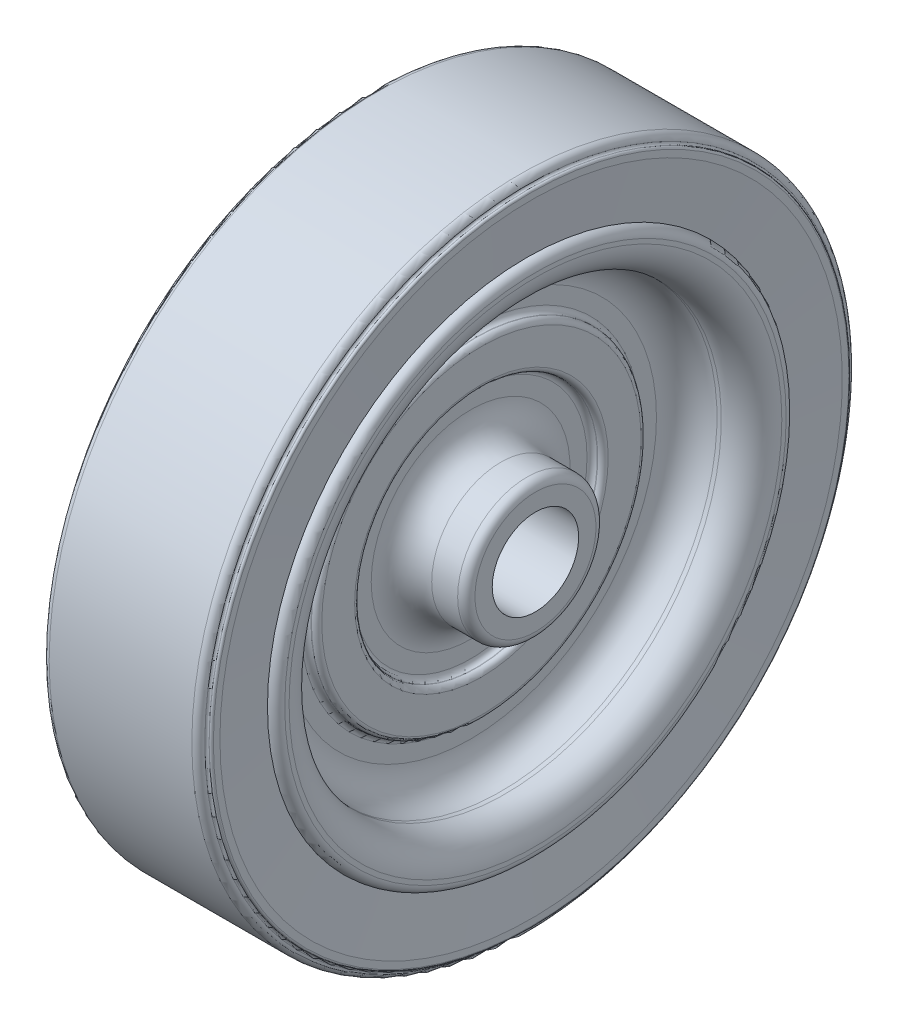
SolidWorks part; units mm, degrees
ref_plane "Front Plane" through (0, 0, 0) normal (0, 0, 1) x (1, 0, 0)
ref_plane "Top Plane" through (0, 0, 0) normal (0, 1, 0) x (1, 0, 0)
ref_plane "Right Plane" through (0, 0, 0) normal (1, 0, 0) x (0, 0, -1)
sketch "Sketch1" plane through (0, 0, 0) normal (0, 0, 1) x (1, 0, 0)
  line L0 (-29.5073, 0) -> (47.8198, 0) construction
  line L1 (4.9928, 38.1359) -> (5.0928, 38.1359)
  line L2 (-19.2072, 16) -> (-13.2072, 16)
  line L3 (-21.2072, 14) -> (-21.2072, 10)
  line L4 (-21.2072, 10) -> (18.7928, 10)
  line L5 (18.7928, 14) -> (18.7928, 10)
  line L9 (-6.2072, 23) -> (-6.2072, 26.9359)
  line L10 (10.7928, 16) -> (16.7928, 16)
  line L11 (3.7928, 23) -> (3.7928, 26.9359)
  line L12 (-14.2072, 50) -> (-13.2072, 50)
  line L13 (-21.2072, 57) -> (-21.2072, 58)
  line L14 (-19.2072, 60) -> (16.7928, 60)
  line L15 (18.7928, 57) -> (18.7928, 58)
  line L16 (-7.5072, 38.1359) -> (-7.4072, 38.1359)
  line L17 (-8.7072, 36.9359) -> (-8.7072, 29.3359)
  line L18 (-7.5072, 28.1359) -> (-7.4072, 28.1359)
  line L19 (6.2928, 36.9359) -> (6.2928, 29.3359)
  line L20 (10.7928, 50) -> (11.7928, 50)
  line L22 (-6.2072, 39.3359) -> (-6.2072, 43)
  line L24 (4.9928, 28.1359) -> (5.0928, 28.1359)
  line L25 (3.7928, 39.3359) -> (3.7928, 43)
  arc A0 (16.7928, 16) -> (18.7928, 14) centre (16.7928, 14) cw
  arc A1 (-19.2072, 16) -> (-21.2072, 14) centre (-19.2072, 14) ccw
  arc A2 (16.7928, 60) -> (18.7928, 58) centre (16.7928, 58) cw
  arc A3 (-21.2072, 58) -> (-19.2072, 60) centre (-19.2072, 58) cw
  arc A4 (10.7928, 16) -> (3.7928, 23) centre (10.7928, 23) cw
  arc A5 (-13.2072, 16) -> (-6.2072, 23) centre (-13.2072, 23) ccw
  arc A6 (11.7928, 50) -> (18.7928, 57) centre (11.7928, 57) ccw
  arc A7 (3.7928, 43) -> (10.7928, 50) centre (10.7928, 43) cw
  arc A8 (-13.2072, 50) -> (-6.2072, 43) centre (-13.2072, 43) cw
  arc A9 (-14.2072, 50) -> (-21.2072, 57) centre (-14.2072, 57) cw
  arc A10 (4.9928, 38.1359) -> (3.7928, 39.3359) centre (4.9928, 39.3359) cw
  arc A11 (5.0928, 38.1359) -> (6.2928, 36.9359) centre (5.0928, 36.9359) cw
  arc A12 (5.0928, 28.1359) -> (6.2928, 29.3359) centre (5.0928, 29.3359) ccw
  arc A13 (4.9928, 28.1359) -> (3.7928, 26.9359) centre (4.9928, 26.9359) ccw
  arc A14 (-7.4072, 28.1359) -> (-6.2072, 26.9359) centre (-7.4072, 26.9359) cw
  arc A15 (-8.7072, 29.3359) -> (-7.5072, 28.1359) centre (-7.5072, 29.3359) ccw
  arc A16 (-7.5072, 38.1359) -> (-8.7072, 36.9359) centre (-7.5072, 36.9359) ccw
  arc A17 (-7.4072, 38.1359) -> (-6.2072, 39.3359) centre (-7.4072, 39.3359) ccw
  point P3 (-1.2072, 13)
  point P16 (-1.2072, 33.1359)
  point P25 (18.7928, 16)
  point P32 (18.7928, 60)
  point P35 (-21.2072, 60)
  point P38 (3.7928, 16)
  point P43 (18.7928, 50)
  point P46 (3.7928, 50)
  point P49 (-6.2072, 50)
  point P54 (3.7928, 38.1359)
  point P57 (6.2928, 38.1359)
  point P66 (-8.7072, 28.1359)
  point P69 (-8.7072, 38.1359)
  point P72 (-6.2072, 38.1359)
  dimension "D12" = 2
  dimension "D15" = 7
  dimension "D16" = 1.2
  dimension "D1" = 40
  dimension "D2" = 10
  dimension "D3" = 6
  dimension "D4" = 15
  dimension "D5" = 10
  dimension "D6" = 34
  dimension "D7" = 10
  dimension "D8" = 15
  dimension "D9" = 20
  dimension "D10" = 40
  dimension "D11" = 10
  dimension "D13" = 15
  dimension "D14" = 15
revolve "Revolve1" add sketch "Sketch1" angle 360 about L0
sketch "Sketch2" plane through (0, 0, 0) normal (0, 0, 1) x (1, 0, 0)
  line L0 (-20.2072, 72) -> (-19.2072, 60)
  line L1 (-19.2072, 60) -> (16.7928, 60)
  line L2 (-19.2072, 74.4887) -> (-19.2072, 74.5)
  line L3 (-17.7072, 76) -> (15.2928, 76)
  line L4 (16.7928, 74.49) -> (16.7928, 74.5)
  line L5 (-19.7185, 74) -> (-19.6959, 74)
  line L6 (-20.2072, 73.5113) -> (-20.2072, 72)
  line L7 (-37.5061, 0) -> (46.3899, 0) construction
  line L8 (17.7928, 73.51) -> (17.7928, 72)
  line L9 (16.7928, 60) -> (17.7928, 72)
  line L11 (17.2828, 74) -> (17.3028, 74)
  arc A0 (-19.2072, 74.4887) -> (-19.6959, 74) centre (-19.6959, 74.4887) cw
  arc A1 (-19.7185, 74) -> (-20.2072, 73.5113) centre (-19.7185, 73.5113) ccw
  arc A2 (17.3028, 74) -> (17.7928, 73.51) centre (17.3028, 73.51) cw
  arc A3 (17.2828, 74) -> (16.7928, 74.49) centre (17.2828, 74.49) cw
  arc A4 (15.2928, 76) -> (16.7928, 74.5) centre (15.2928, 74.5) cw
  arc A5 (-19.2072, 74.5) -> (-17.7072, 76) centre (-17.7072, 74.5) cw
  point P19 (17.7928, 74)
  point P24 (16.7928, 76)
  point P27 (-19.2072, 76)
  dimension "D7" = 0.4887
  dimension "D8" = 0.49
  dimension "D1" = 1.5
  dimension "D2" = 36
  dimension "D3" = 1
  dimension "D4" = 1
  dimension "D5" = 2
  dimension "D6" = 2
revolve "Revolve2" add sketch "Sketch2" angle 360 about L7
